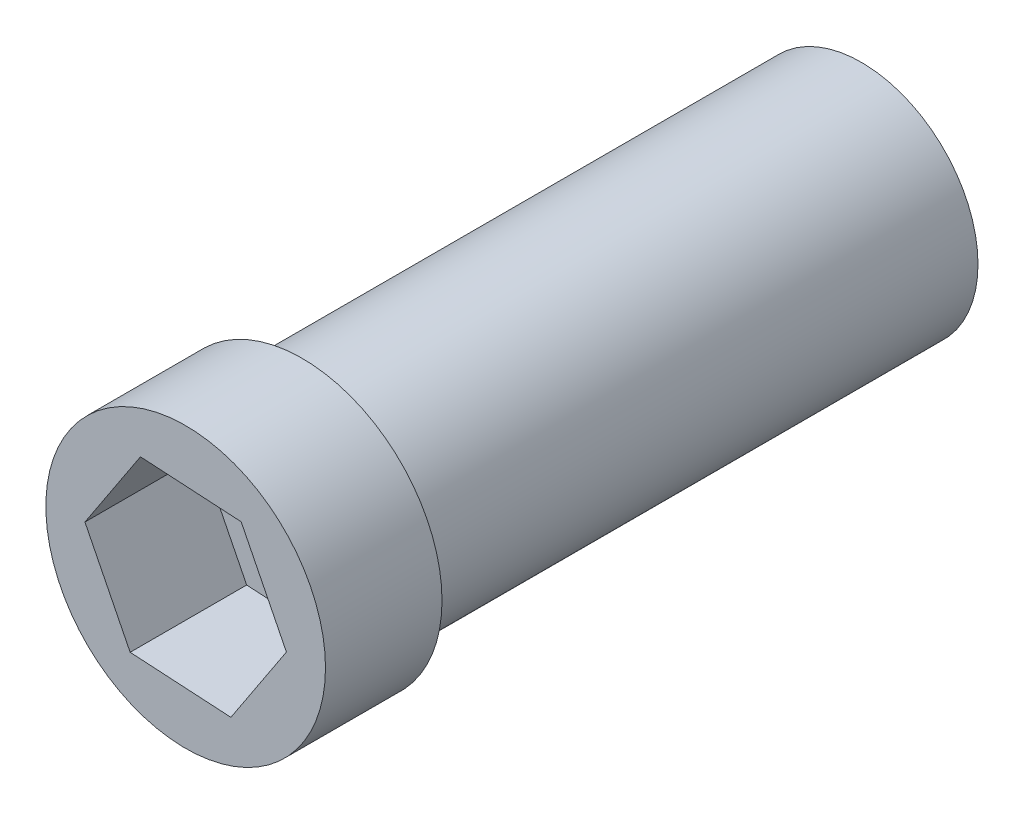
SolidWorks part; units mm, degrees
material "AISI 304"
ref_plane "Alzado" through (0, 0, 0) normal (0, 0, 1) x (1, 0, 0)
ref_plane "Planta" through (0, 0, 0) normal (0, 1, 0) x (1, 0, 0)
ref_plane "Vista lateral" through (0, 0, 0) normal (1, 0, 0) x (0, 0, -1)
sketch "Croquis1" plane through (0, 0, 0) normal (0, 0, 1) x (1, 0, 0)
  circle A0 centre (0, 0) radius 3.175
  dimension "D1" = 6.35
extrude "Saliente-Extruir1" add sketch "Croquis1" against normal blind 15.24
sketch "Croquis2" plane through (0, 0, 0) normal (0, 0, 1) x (1, 0, 0)
  circle A0 centre (0, 0) radius 3.81
  dimension "D1" = 7.62
extrude "Saliente-Extruir2" add sketch "Croquis2" along normal blind 3.175
sketch "Croquis3" plane through (0, 0, 3.175) normal (0, 0, 1) x (1, 0, 0)
  line L1 (-2.7449, 0.1619) -> (-1.5127, -2.2962)
  line L2 (-1.5127, -2.2962) -> (1.2322, -2.4581)
  line L3 (1.2322, -2.4581) -> (2.7449, -0.1619)
  line L4 (2.7449, -0.1619) -> (1.5127, 2.2962)
  line L5 (1.5127, 2.2962) -> (-1.2322, 2.4581)
  line L6 (-1.2322, 2.4581) -> (-2.7449, 0.1619)
  circle A0 centre (0, 0) radius 2.3813 construction
  dimension "D1" = 4.7625
extrude "Cortar-Extruir1" cut sketch "Croquis3" against normal blind 3.175
